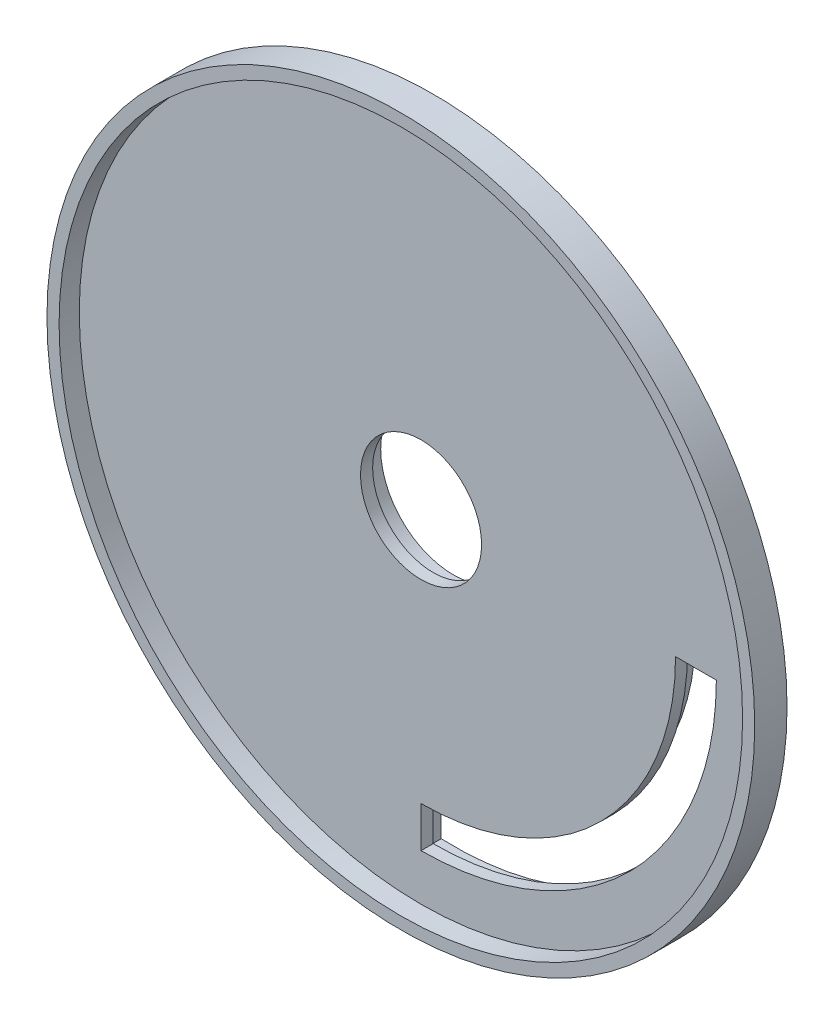
SolidWorks part; units mm, degrees
ref_plane "정면" through (0, 0, 0) normal (0, 0, 1) x (1, 0, 0)
ref_plane "윗면" through (0, 0, 0) normal (0, 1, 0) x (1, 0, 0)
ref_plane "우측면" through (0, 0, 0) normal (1, 0, 0) x (0, 0, -1)
sketch "스케치1" plane through (0, 0, 0) normal (0, 0, 1) x (1, 0, 0)
  circle A0 centre (0, 0) radius 87.6
  point P2 (0, 0)
  dimension "D1" = 175.2
extrude "보스-돌출1" add sketch "스케치1" along normal blind 3
sketch "스케치3" plane through (0, 0, 3) normal (0, 0, 1) x (1, 0, 0)
  circle A0 centre (0, 0) radius 84.6
  circle A1 centre (0, 0) radius 87.6
  circle A2 centre (0, 0) radius 87.6
  dimension "D2" = 169.2
  dimension "D1" = 0
extrude "보스-돌출2" add sketch "스케치3" along normal blind 5
sketch "스케치4" plane through (0, 0, 0) normal (0, 0, -1) x (-1, 0, 0)
  line L0 (-59.925, 3) -> (-76.0408, 3)
  line L1 (3, -76.0408) -> (3, -59.925)
  line L2 (-63, 0) -> (-73.1, 0)
  line L3 (0, -73.1) -> (0, -63)
  arc A0 (-59.925, 3) -> (3, -59.925) centre (0, 0) ccw
  arc A1 (-76.0408, 3) -> (3, -76.0408) centre (0, 0) ccw
  arc A2 (-73.1, 0) -> (0, -73.1) centre (0, 0) ccw
  arc A3 (-63, 0) -> (0, -63) centre (0, 0) ccw
  point P6 (0, 0)
  dimension "D1" = 60
  dimension "D2" = 76.1
  dimension "D3" = 16.1159
  dimension "D4" = 16.1159
  dimension "D5" = 3
extrude "컷-돌출1" cut sketch "스케치4" against normal blind 5 contours L2 A2 L3 A3
sketch "스케치5" plane through (0, 0, 0) normal (0, 0, -1) x (-1, 0, 0)
  line L0 (-59.925, 3) -> (-76.0408, 3)
  line L1 (3, -76.0408) -> (3, -59.925)
  line L4 (6, -78.8721) -> (6, -56.6833)
  line L5 (-56.6833, 6) -> (-78.8721, 6)
  arc A0 (-59.925, 3) -> (3, -59.925) centre (0, 0) ccw
  arc A1 (-76.0408, 3) -> (3, -76.0408) centre (0, 0) ccw
  arc A4 (-56.6833, 6) -> (6, -56.6833) centre (0, 0) ccw
  arc A5 (-78.8721, 6) -> (6, -78.8721) centre (0, 0) ccw
  point P2 (0, 0)
  dimension "D1" = 60
  dimension "D2" = 76.1
  dimension "D3" = 16.1159
  dimension "D4" = 16.1159
  dimension "D5" = 3
extrude "보스-돌출3" add sketch "스케치5" along normal blind 5
sketch "스케치6" plane through (0, 0, 0) normal (0, 0, -1) x (-1, 0, 0)
  circle A0 centre (0, 0) radius 17.9826
  circle A1 centre (0, 0) radius 14.9826
  point P4 (0, 0)
  point P6 (0, 0)
  point P7 (0, -0.5512)
  dimension "D1" = 35.9652
  dimension "D2" = 29.9652
extrude "컷-돌출2" cut sketch "스케치6" against normal blind 5 contours A1
sketch "스케치7" plane through (0, 0, 0) normal (0, 0, -1) x (-1, 0, 0)
  circle A0 centre (0, 0) radius 17.9826
  circle A1 centre (0, 0) radius 14.9826
  circle A2 centre (0, 0) radius 20.9826
  point P3 (0, 0)
  dimension "D1" = 35.9652
  dimension "D2" = 29.9652
  dimension "D3" = 3
extrude "보스-돌출4" add sketch "스케치7" along normal blind 5 contours A2 A0
